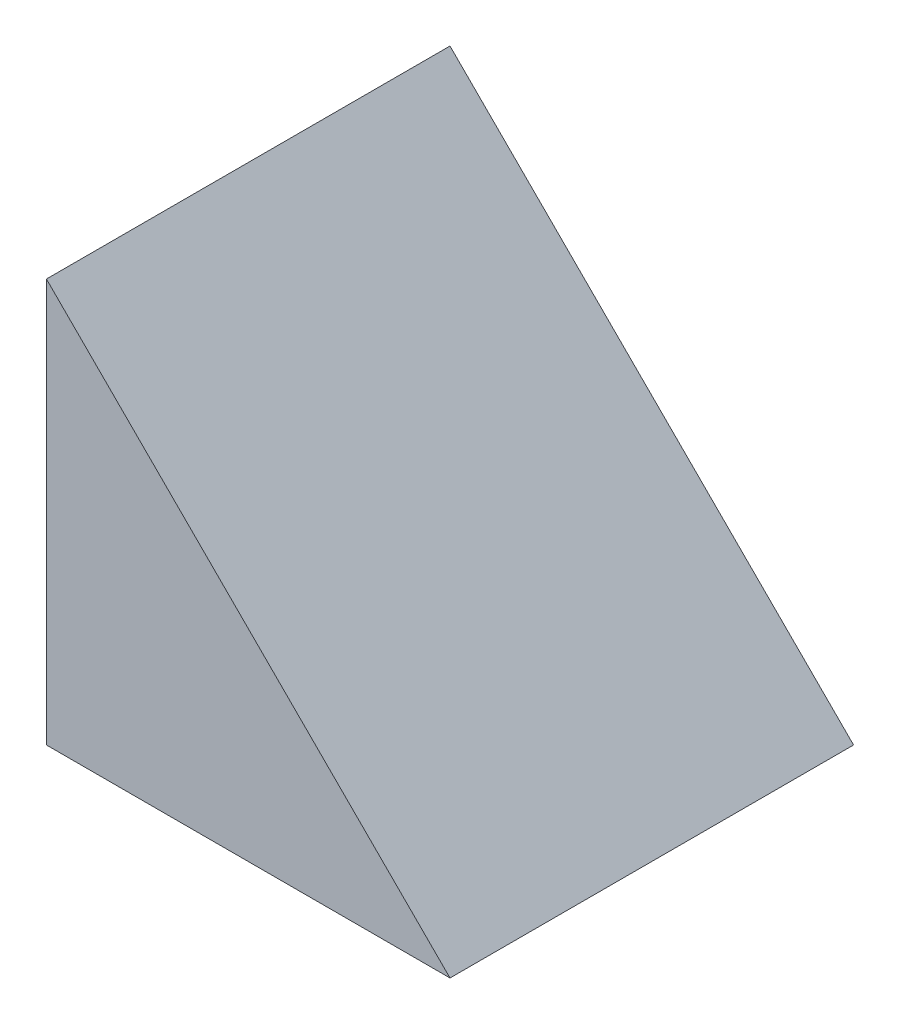
SolidWorks part; units mm, degrees
material "Maple"
ref_plane "Front" through (0, 0, 0) normal (0, 0, 1) x (1, 0, 0)
ref_plane "Top" through (0, 0, 0) normal (0, 1, 0) x (1, 0, 0)
ref_plane "Right" through (0, 0, 0) normal (1, 0, 0) x (0, 0, -1)
sketch "Sketch1" plane through (0, 0, 0) normal (0, 0, 1) x (1, 0, 0)
  line L0 (0, 0) -> (114.3, 0)
  line L3 (0, 0) -> (0, 114.3)
  line L4 (0, 114.3) -> (114.3, 0)
  dimension "D1" = 114.3
  dimension "D2" = 114.3
extrude "Boss-Extrude1" add sketch "Sketch1" along normal blind 114.3
